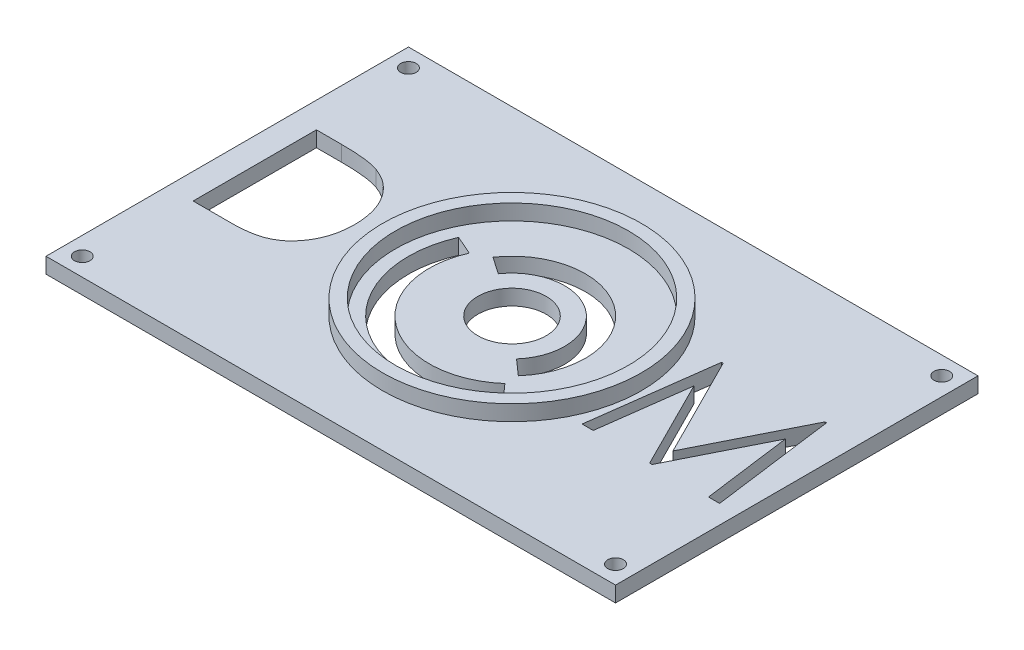
SolidWorks part; units mm, degrees
ref_plane "Front Plane" through (0, 0, 0) normal (0, 0, 1) x (1, 0, 0)
ref_plane "Top Plane" through (0, 0, 0) normal (0, 1, 0) x (1, 0, 0)
ref_plane "Right Plane" through (0, 0, 0) normal (1, 0, 0) x (0, 0, -1)
sketch "Sketch1" plane through (0, 0, 0) normal (0, 1, 0) x (1, 0, 0)
  line L1 (-59.9593, 47.2358) -> (50.0407, 47.2358)
  line L2 (-59.9593, 47.2358) -> (-59.9593, -22.7642)
  line L3 (-59.9593, -22.7642) -> (50.0407, -22.7642)
  line L4 (50.0407, 47.2358) -> (50.0407, -22.7642)
  dimension "D1" = 70
  dimension "D2" = 110
extrude "Boss-Extrude1" add sketch "Sketch1" along normal blind 6
sketch "Sketch2" plane through (0, 6, 0) normal (0, 1, 0) x (1, 0, 0)
  line L0 (-59.9593, 47.2358) -> (-59.9593, -22.7642) construction
  line L1 (-59.9593, -22.7642) -> (50.0407, -22.7642) construction
  circle A0 centre (-4.9593, 12.2358) radius 22.5
  point P2 (-59.9593, 12.2358)
  point P7 (-4.9593, -22.7642)
  dimension "D1" = 45
  dimension "D2" = 0
  dimension "D3" = 0
extrude "Cut-Extrude1" cut sketch "Sketch2" against normal blind 3
sketch "Sketch3" plane through (0, 3, 0) normal (0, 1, 0) x (1, 0, 0)
  circle A0 centre (-4.9593, 12.2358) radius 6.6
  dimension "D1" = 13.2
extrude "Cut-Extrude2" cut sketch "Sketch3" against normal blind 3.2
sketch "Sketch4" plane through (0, 6, 0) normal (0, 1, 0) x (1, 0, 0)
  line L1 (-59.9593, 47.2358) -> (50.0407, 47.2358)
  line L2 (-59.9593, 47.2358) -> (-59.9593, -22.7642)
  line L3 (-59.9593, -22.7642) -> (50.0407, -22.7642)
  line L4 (50.0407, 47.2358) -> (50.0407, -22.7642)
  circle A0 centre (-4.9593, 12.2358) radius 25
  dimension "D1" = 50
extrude "Cut-Extrude3" cut sketch "Sketch4" against normal blind 3
sketch "Sketch5" plane through (0, 3, 0) normal (0, 1, 0) x (1, 0, 0)
  line L0 (50.0407, 47.2358) -> (-59.9593, 47.2358) construction
  line L1 (-59.9593, 47.2358) -> (-59.9593, -22.7642) construction
  line L2 (-59.9593, -22.7642) -> (50.0407, -22.7642) construction
  line L3 (-59.9593, 47.2358) -> (-59.9593, -22.7642) construction
  line L4 (50.0407, -22.7642) -> (50.0407, 47.2358) construction
  circle A0 centre (-56.4593, 43.7358) radius 1.5
  circle A1 centre (-56.4593, -19.2642) radius 1.5
  circle A2 centre (46.5407, -19.2642) radius 1.5
  circle A3 centre (46.5407, 43.7358) radius 1.5
  dimension "D1" = 3.5
  dimension "D2" = 3.5
  dimension "D3" = 3
  dimension "D4" = 3
  dimension "D5" = 3.5
  dimension "D6" = 3.5
  dimension "D7" = 3
  dimension "D8" = 3.5
  dimension "D9" = 3.5
  dimension "D10" = 3.5
  dimension "D11" = 3.5
  dimension "D12" = 3
extrude "Cut-Extrude4" cut sketch "Sketch5" against normal through all
sketch "Sketch6" plane through (0, 3, 0) normal (0, 1, 0) x (1, 0, 0)
  line L2 (-16.6403, 20.2395) -> (-13.3406, 17.9786)
  line L3 (5.6442, 2.8512) -> (2.6488, 5.5022)
  line L4 (-23.2771, 20.2395) -> (-19.6117, 18.638)
  line L5 (5.6442, 0.2673) -> (8.2967, -2.7267)
  circle A0 centre (-4.9593, 12.2358) radius 17.99 construction
  circle A1 centre (-4.9593, 12.2358) radius 12.16 construction
  arc A4 (-23.2771, 20.2395) -> (8.2967, -2.7267) centre (-4.9593, 12.2358) ccw
  arc A5 (-19.6117, 18.638) -> (5.6442, 0.2673) centre (-4.9593, 12.2358) ccw
  arc A6 (5.6442, 2.8512) -> (-16.6403, 20.2395) centre (-4.9593, 12.2358) ccw
  arc A7 (2.6488, 5.5022) -> (-13.3406, 17.9786) centre (-4.9593, 12.2358) ccw
  dimension "D1" = 35.98
  dimension "D2" = 24.32
  dimension "D3" = 2
  dimension "D4" = 2
  dimension "D5" = 2
  dimension "D6" = 2
extrude "Cut-Extrude5" cut sketch "Sketch6" against normal blind 5 contours A6 A7 | A4 A5
sketch "Sketch7" plane through (0, 3, 0) normal (0, 1, 0) x (1, 0, 0)
  line L0 (50.0407, -22.7642) -> (50.0407, 47.2358) construction
  text T0 "D" font "Century Gothic" height in points 90
  text T1 "M" font "Century Gothic" height in points 90
  dimension "D1" = 32
extrude "Cut-Extrude6" cut sketch "Sketch7" against normal blind 11.5
